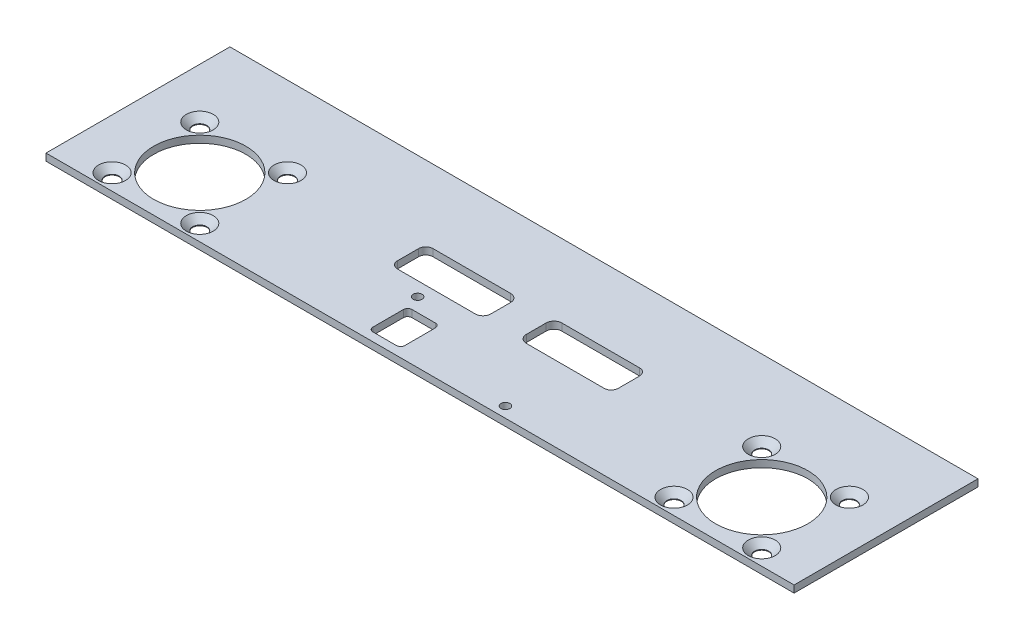
SolidWorks part; units mm, degrees
ref_plane "前视基准面" through (0, 0, 0) normal (0, 0, 1) x (1, 0, 0)
ref_plane "上视基准面" through (0, 0, 0) normal (0, 1, 0) x (1, 0, 0)
ref_plane "右视基准面" through (0, 0, 0) normal (1, 0, 0) x (0, 0, -1)
sketch "草图1" plane through (0, 0, 0) normal (0, 1, 0) x (1, 0, 0)
  line L1 (0, 0) -> (196, 0)
  line L2 (0, 0) -> (0, 41.87)
  line L3 (0, 41.87) -> (196, 41.87)
  line L4 (196, 0) -> (196, 41.87)
  dimension "D1" = 41.87
  dimension "D2" = 196
extrude "凸台-拉伸1" add sketch "草图1" along normal blind 2
sketch "草图2" plane through (0, 2, 0) normal (0, 1, 0) x (1, 0, 0)
  line L0 (0, 41.87) -> (0.5, 41.87) construction
  line L1 (26.5, 16.87) -> (52.5, 16.87) construction
  line L2 (196, 41.87) -> (0, 41.87) construction
  line L3 (0.5, 41.87) -> (0.5, 0) construction
  line L4 (0, 0) -> (196, 0) construction
  line L5 (0.5, 0) -> (52.5, 0) construction
  line L6 (52.5, 0) -> (52.5, 41.87) construction
  line L7 (52.5, 41.87) -> (0.5, 41.87) construction
  line L8 (196, 41.87) -> (196, 0) construction
  line L9 (196, 0) -> (144, 0) construction
  line L10 (144, 0) -> (144, 41.87) construction
  line L11 (144, 41.87) -> (196, 41.87) construction
  line L12 (26.5, 41.87) -> (26.5, 16.87) construction
  line L13 (0.5, 41.87) -> (13.13, 41.87) construction
  line L15 (170, 41.87) -> (170, 16.87) construction
  line L16 (170, 16.87) -> (196, 16.87) construction
  line L17 (144, 41.87) -> (157.63, 41.87) construction
  line L18 (157.63, 41.87) -> (157.63, 29.24) construction
  circle A0 centre (26.5, 16.87) radius 13
  circle A1 centre (14.13, 29.24) radius 2
  circle A2 centre (38.87, 29.24) radius 2
  circle A3 centre (38.87, 4.5) radius 2
  circle A4 centre (14.13, 4.5) radius 2
  circle A5 centre (170, 16.87) radius 13
  circle A6 centre (157.63, 29.24) radius 2
  circle A7 centre (182.37, 29.24) radius 2
  circle A8 centre (182.37, 4.5) radius 2
  circle A9 centre (157.63, 4.5) radius 2
  dimension "D5" = 26
  dimension "D8" = 4
  dimension "D10" = 26
  dimension "D13" = 4
  dimension "D6" = 12.37
  dimension "D7" = 12.37
  dimension "D11" = 12.37
  dimension "D12" = 12.37
  dimension "D1" = 0.5
  dimension "D2" = 52
  dimension "D3" = 52
  dimension "D4" = 25
  dimension "D9" = 25
extrude "切除-拉伸1" cut sketch "草图2" against normal blind 40
sketch "草图3" plane through (0, 2, 0) normal (0, 1, 0) x (1, 0, 0)
  line L0 (0, 41.87) -> (99.55, 41.87) construction
  line L1 (196, 41.87) -> (0, 41.87) construction
  line L2 (99.55, 41.87) -> (99.55, 0) construction
  line L3 (0, 0) -> (196, 0) construction
  line L4 (122.65, 0) -> (76.45, 0)
  line L5 (76.45, 0) -> (76.45, 20.4)
  line L6 (76.45, 20.4) -> (122.65, 20.4)
  line L7 (122.65, 0) -> (122.65, 20.4)
  line L8 (0, 41.87) -> (68.03, 41.87) construction
  line L9 (68.03, 41.87) -> (68.03, 33.87)
  line L10 (78.03, 23.87) -> (121.03, 23.87)
  line L11 (131.03, 33.87) -> (131.03, 41.87)
  line L12 (131.03, 41.87) -> (68.03, 41.87)
  arc A0 (131.03, 33.87) -> (121.03, 23.87) centre (121.03, 33.87) cw
  arc A1 (78.03, 23.87) -> (68.03, 33.87) centre (78.03, 33.87) cw
  point P13 (99.55, 20.4)
  point P19 (131.03, 23.87)
  point P22 (68.03, 23.87)
  dimension "D7" = 10
  dimension "D1" = 99.55
  dimension "D2" = 23.1
  dimension "D3" = 20.4
  dimension "D4" = 68.03
  dimension "D5" = 18
  dimension "D6" = 63
extrude "切除-拉伸2" cut sketch "草图3" against normal blind 218 contours L12 L9 A1 L10 A0 L11
sketch "草图6" plane through (0, 2, 0) normal (0, 1, 0) x (1, 0, 0)
  line L0 (99.55, 0) -> (99.55, 67.4388) construction
  line L1 (77.52, 0) -> (121.58, 0)
  line L2 (0, 0) -> (196, 0) construction
  line L3 (121.58, 0) -> (121.58, 20.3)
  line L4 (121.58, 20.3) -> (77.52, 20.3)
  line L5 (77.52, 0) -> (77.52, 20.3)
  line L6 (121.58, 20.3) -> (117.98, 20.3)
  line L7 (81.12, 6.9) -> (90.12, 6.9)
  line L8 (117.98, 17.9) -> (108.98, 17.9) construction
  line L9 (108.98, 17.9) -> (108.98, 6.9) construction
  line L10 (117.98, 17.9) -> (117.98, 6.9) construction
  line L11 (117.98, 6.9) -> (108.98, 6.9) construction
  line L12 (81.12, 17.9) -> (81.12, 6.9)
  line L13 (90.12, 17.9) -> (90.12, 6.9)
  line L14 (81.12, 17.9) -> (90.12, 17.9)
  point P10 (99.55, 20.3)
  dimension "D1" = 22.03
  dimension "D2" = 20.3
  dimension "D3" = 3.6
  dimension "D4" = 2.4
  dimension "D5" = 9
  dimension "D6" = 11
sketch "草图7" plane through (0, 2, 0) normal (0, 1, 0) x (1, 0, 0)
  line L0 (121.58, 0) -> (118.58, 0) construction
  line L1 (0, 0) -> (196, 0) construction
  line L2 (118.58, 0) -> (118.58, 3) construction
  line L3 (77.52, 20.3) -> (80.52, 20.3) construction
  line L4 (80.52, 20.3) -> (80.52, 17.3) construction
  line L5 (99.55, 20.3) -> (99.55, 0) construction
  circle A1 centre (80.52, 17.3) radius 1.25 construction
  circle A2 centre (118.58, 3) radius 1.25 construction
  circle A5 centre (80.02, 3) radius 1.25
  circle A6 centre (119.08, 17.3) radius 1.25
  dimension "D3" = 3
  dimension "D5" = 2.5
  dimension "D6" = 2.5
  dimension "D8" = 2.5
  dimension "D9" = 2.5
  dimension "D1" = 3
  dimension "D2" = 3
  dimension "D4" = 3
extrude "切除-拉伸3" cut sketch "草图6" against normal blind 10 contours L14 L12 L7 L13
extrude "切除-拉伸4" cut sketch "草图7" against normal blind 10
sketch "草图8" plane through (0, 2, 0) normal (0, 1, 0) x (1, 0, 0)
  line L0 (68.03, 31.24) -> (131.03, 31.24)
  line L3 (131.03, 41.87) -> (68.03, 41.87)
  line L4 (68.03, 41.87) -> (68.03, 31.24)
  line L5 (131.03, 41.87) -> (131.03, 31.24)
extrude "凸台-拉伸2" add sketch "草图8" against normal up to surface (2 mm away) up to face at (119.08, 0, -18.55)
sketch "草图9" plane through (0, 2, 0) normal (0, 1, 0) x (1, 0, 0)
  line L0 (68.382, 31.24) -> (68.382, 21.24)
  line L1 (68.382, 21.24) -> (130.678, 21.24)
  line L2 (130.678, 21.24) -> (130.678, 31.24)
  line L3 (130.678, 31.24) -> (68.382, 31.24)
  dimension "D1" = 10
extrude "切除-拉伸5" cut sketch "草图9" against normal blind 10
fillet "圆角1" radius 2 4 edges at (68.382, 1, -21.24) (130.678, 1, -21.24) (130.678, 1, -31.24) (68.382, 1, -31.24)
fillet "圆角2" radius 1.2 4 edges at (81.12, 1, -6.9) (90.12, 1, -6.9) (90.12, 1, -17.9) (81.12, 1, -17.9)
hole_wizard "打孔尺寸(%根据)内六角花形半沉头螺钉的类型1" positions "3D草图1" profile "草图10" countersink size "M6" standard "GB"
sketch3d "3D草图1"
  line L0 (157.63, 0, -29.24) -> (157.63, 2, -29.24) construction
  line L1 (182.37, 0, -29.24) -> (182.37, 2, -29.24) construction
  line L2 (157.63, 0, -4.5) -> (157.63, 2, -4.5) construction
  line L3 (182.37, 0, -4.5) -> (182.37, 2, -4.5) construction
  point P0 (182.37, 2, -29.24)
  point P3 (157.63, 2, -29.24)
  point P6 (157.63, 2, -4.5)
  point P9 (182.37, 2, -4.5)
  point P12 (38.87, 2, -29.24)
  point P15 (38.87, 2, -4.5)
  point P18 (14.13, 2, -4.5)
  point P21 (14.13, 2, -29.24)
  point P24 (157.63, 2, -29.24)
  point P28 (182.37, 0, -29.24)
  point P32 (157.63, 2, -4.5)
  point P36 (182.37, 0, -4.5)
  point P40 (182.37, 0, -29.24)
  point P43 (157.63, 2, -29.24)
  point P45 (157.63, 2, -4.5)
  point P47 (182.37, 0, -4.5)
  point P49 (182.37, 0, -29.24)
sketch "草图10" plane through (182.37, 2, -29.24) normal (1, 0, 0) x (0, 0, 1)
  line L0 (0, 0) -> (0, 5.0017)
  line L1 (0, 5.0017) -> (2, 3.8)
  line L2 (2, 3.8) -> (2, 1.8)
  line L3 (2, 1.8) -> (3.8, 0)
  line L5 (3.8, 0) -> (0, 0)
  line L6 (-2, 1.8) -> (-3.8, 0) construction
  line L10 (0, 5.0017) -> (-2, 3.8) construction
  line L11 (0, -6.35) -> (0, 107.95) construction
  dimension "孔直径" = 4
  dimension "孔深度" = 3.8
  dimension "近端锥形沉头孔直径" = 7.6
  dimension "近端锥形沉头孔角度" = 90
  dimension "导头角度" = 118
sketch "草图14" plane through (0, 2, 0) normal (0, 1, 0) x (1, 0, 0)
  line L4 (77.52, 10.15) -> (124.0678, 10.15) construction
  line L5 (77.52, 0) -> (77.52, 20.3) construction
  line L6 (90.12, 13.4) -> (81.12, 13.4)
  line L7 (90.12, 2.4) -> (90.12, 13.4)
  line L8 (81.12, 2.4) -> (90.12, 2.4)
  line L9 (81.12, 13.4) -> (81.12, 2.4)
  circle A1 centre (80.02, 17.3) radius 1.25
  circle A3 centre (119.08, 3) radius 1.25
extrude "切除-拉伸8" cut sketch "草图14" against normal blind 10
sketch "草图15" plane through (0, 2, 0) normal (0, 1, 0) x (1, 0, 0)
  line L0 (81.12, 13.4) -> (90.12, 13.4)
  line L1 (90.12, 13.4) -> (90.12, 17.9)
  line L2 (90.12, 17.9) -> (81.12, 17.9)
  line L3 (81.12, 17.9) -> (81.12, 13.4)
  circle A0 centre (80.02, 3) radius 1.25
  circle A1 centre (119.08, 17.3) radius 1.25
extrude "凸台-拉伸4" add sketch "草图15" against normal up to surface (2 mm away)
sketch "草图16" plane through (0, 2, 0) normal (0, 1, 0) x (1, 0, 0)
  line L0 (81.12, 13.4) -> (90.12, 13.4)
  line L1 (90.12, 13.4) -> (90.12, 2.4)
  line L2 (90.12, 2.4) -> (81.12, 2.4063)
  line L3 (81.12, 2.4063) -> (81.12, 13.4)
  circle A0 centre (80.02, 17.3) radius 1.25
  dimension "D1" = 2.5
extrude "切除-拉伸9" cut sketch "草图16" against normal blind 10
fillet "圆角3" radius 1.2 4 edges at (90.12, 1, -2.4) (81.12, 1, -2.4) (90.12, 1, -13.4) (81.12, 1, -13.4)
sketch "草图17" plane through (0, 2, 0) normal (0, 1, 0) x (1, 0, 0)
  line L0 (196, 41.87) -> (211, 41.87)
  line L1 (211, 41.87) -> (211, 0)
  line L2 (211, 0) -> (196, 0)
  line L3 (196, 0) -> (196, 41.87)
  dimension "D1" = 15
extrude "凸台-拉伸5" add sketch "草图17" against normal up to surface (2 mm away)
sketch "草图18" plane through (0, 2, 0) normal (0, 1, 0) x (1, 0, 0)
  line L0 (170, 16.87) -> (185, 16.87) construction
  line L1 (170, 16.87) -> (196, 16.87) construction
  line L2 (77.882, 21.24) -> (136.178, 21.24)
  line L3 (88.62, 12.2) -> (88.62, 3.6)
  line L4 (97.62, 12.2) -> (97.62, 3.6)
  line L5 (70.382, 21.24) -> (128.678, 21.24) construction
  line L6 (89.82, 13.4) -> (96.42, 13.4)
  line L7 (89.82, 2.4) -> (96.42, 2.4)
  line L9 (136.178, 31.24) -> (77.882, 31.24)
  line L10 (75.882, 29.24) -> (75.882, 23.24)
  line L11 (138.178, 23.24) -> (138.178, 29.24)
  circle A0 centre (185, 16.87) radius 13
  circle A1 centre (172.63, 29.24) radius 2
  circle A2 centre (197.37, 29.24) radius 2
  circle A3 centre (197.37, 4.5) radius 2
  circle A4 centre (172.63, 4.5) radius 2
  circle A6 centre (126.58, 3) radius 1.25
  arc A7 (89.82, 13.4) -> (88.62, 12.2) centre (89.82, 12.2) ccw
  arc A8 (96.42, 13.4) -> (97.62, 12.2) centre (96.42, 12.2) cw
  arc A9 (97.62, 3.6) -> (96.42, 2.4) centre (96.42, 3.6) cw
  arc A10 (88.62, 3.6) -> (89.82, 2.4) centre (89.82, 3.6) ccw
  arc A13 (77.882, 31.24) -> (75.882, 29.24) centre (77.882, 29.24) ccw
  arc A14 (75.882, 23.24) -> (77.882, 21.24) centre (77.882, 23.24) ccw
  arc A15 (136.178, 31.24) -> (138.178, 29.24) centre (136.178, 29.24) cw
  arc A16 (138.178, 23.24) -> (136.178, 21.24) centre (136.178, 23.24) cw
  circle A17 centre (87.52, 17.3) radius 1.25
  dimension "D2" = 26
  dimension "D7" = 4
  dimension "D8" = 4
  dimension "D9" = 4
  dimension "D10" = 4
  dimension "D6" = 2.5
  dimension "D5" = 2.5
  dimension "D1" = 15
sketch "草图19" plane through (0, 2, 0) normal (0, 1, 0) x (1, 0, 0)
  line L5 (64.2973, 41.87) -> (64.2973, 0)
  line L6 (0, 41.87) -> (196, 41.87) construction
  line L7 (0, 0) -> (196, 0) construction
  line L8 (64.2973, 0) -> (193.2795, 0)
  line L9 (193.2795, 0) -> (193.2795, 41.87)
  line L10 (193.2795, 41.87) -> (64.2973, 41.87)
extrude "凸台-拉伸6" add sketch "草图19" against normal up to surface (2 mm away)
extrude "切除-拉伸10" cut sketch "草图18" against normal blind 24.95
hole_wizard "打孔尺寸(%根据)内六角花形半沉头螺钉的类型2" positions "3D草图2" profile "草图20" countersink size "M6" standard "GB"
sketch3d "3D草图2"
  line L0 (172.63, 0, -29.24) -> (172.63, 2, -29.24) construction
  line L1 (197.37, 0, -29.24) -> (197.37, 2, -29.24) construction
  line L2 (197.37, 0, -4.5) -> (197.37, 2, -4.5) construction
  line L3 (172.63, 0, -4.5) -> (172.63, 2, -4.5) construction
  point P0 (172.63, 2, -29.24)
  point P4 (197.37, 2, -29.24)
  point P8 (197.37, 2, -4.5)
  point P12 (172.63, 2, -4.5)
sketch "草图20" plane through (172.63, 2, -29.24) normal (1, 0, 0) x (0, 0, 1)
  line L0 (0, 0) -> (0, 5.0017)
  line L1 (0, 5.0017) -> (2, 3.8)
  line L2 (2, 3.8) -> (2, 1.8)
  line L3 (2, 1.8) -> (3.8, 0)
  line L5 (3.8, 0) -> (0, 0)
  line L6 (-2, 1.8) -> (-3.8, 0) construction
  line L10 (0, 5.0017) -> (-2, 3.8) construction
  line L11 (0, -6.35) -> (0, 107.95) construction
  dimension "孔直径" = 4
  dimension "孔深度" = 3.8
  dimension "近端锥形沉头孔直径" = 7.6
  dimension "近端锥形沉头孔角度" = 90
  dimension "导头角度" = 118
sketch "草图21" plane through (0, 2, 0) normal (0, 1, 0) x (1, 0, 0)
  line L0 (107.03, 31.24) -> (112.03, 31.24)
  line L1 (136.178, 31.24) -> (77.882, 31.24) construction
  line L2 (112.03, 31.24) -> (112.03, 21.24)
  line L3 (77.882, 21.24) -> (136.178, 21.24) construction
  line L4 (112.03, 21.24) -> (107.03, 21.24)
  line L5 (107.03, 21.24) -> (102.03, 21.24)
  line L6 (102.03, 21.24) -> (102.03, 31.24)
  line L7 (102.03, 31.24) -> (107.03, 31.24)
  dimension "D1" = 5
  dimension "D2" = 5
extrude "凸台-拉伸7" add sketch "草图21" against normal up to surface (2 mm away)
fillet "圆角4" radius 2.2 4 edges at (112.03, 1, -21.24) (112.03, 1, -31.24) (102.03, 1, -21.24) (102.03, 1, -31.24)
sketch "草图25" plane through (0, 2, 0) normal (0, 1, 0) x (1, 0, 0)
  line L1 (0, 41.87) -> (211, 41.87)
  line L2 (0, 41.87) -> (0, 51.87)
  line L3 (0, 51.87) -> (211, 51.87)
  line L4 (211, 41.87) -> (211, 51.87)
  dimension "D1" = 10
extrude "凸台-拉伸8" add sketch "草图25" against normal blind 2 contours L4 L3 L2 L1
